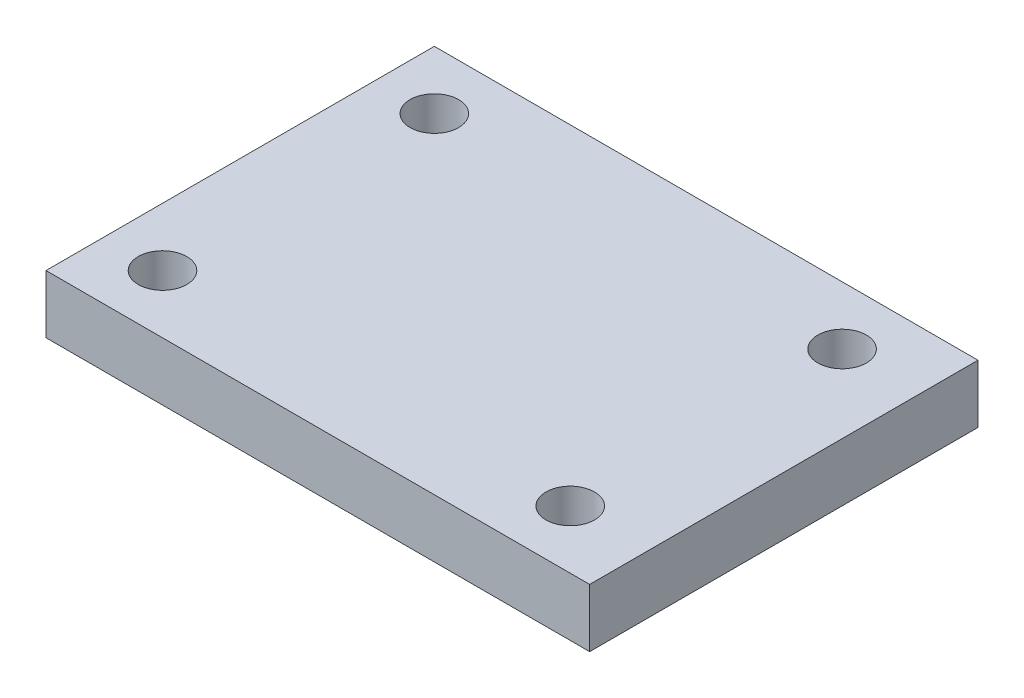
SolidWorks part; units mm, degrees
material "1060 Alloy"
ref_plane "Front Plane" through (0, 0, 0) normal (0, 0, 1) x (1, 0, 0)
ref_plane "Top Plane" through (0, 0, 0) normal (0, 1, 0) x (1, 0, 0)
ref_plane "Right Plane" through (0, 0, 0) normal (1, 0, 0) x (0, 0, -1)
sketch "Sketch1" plane through (0, 0, 0) normal (0, 1, 0) x (1, 0, 0)
  line L1 (-14, -10) -> (14, -10)
  line L2 (-14, -10) -> (-14, 10)
  line L3 (-14, 10) -> (14, 10)
  line L4 (14, -10) -> (14, 10)
  line L5 (-14, -10) -> (14, 10) construction
  line L6 (-14, 10) -> (14, -10) construction
  point P0 (0, 0)
  dimension "D1" = 20
  dimension "D2" = 28
extrude "Boss-Extrude1" add sketch "Sketch1" along normal blind 3
hole_wizard "M3 Tapped Hole1" positions "Sketch2" profile "Sketch3" tap size "M3" standard "DIN" end condition through all
sketch "Sketch2" plane through (0, 3, 0) normal (0, 1, 0) x (1, 0, 0)
  line L0 (-14, 10) -> (-14, -10) construction
  line L1 (14, 10) -> (-14, 10) construction
  point P0 (-11, 7)
  point P2 (10, 7)
  point P4 (10, -7)
  point P6 (-11, -7)
  dimension "D1" = 21
  dimension "D2" = 3
  dimension "D3" = 14
  dimension "D4" = 3
sketch "Sketch3" plane through (-11, 3, -7) normal (1, 0, 0) x (0, 0, 1)
  line L0 (0, 0) -> (0, 3)
  line L1 (0, 3) -> (1.25, 3)
  line L2 (1.25, 3) -> (1.25, 0)
  line L5 (1.25, 0) -> (0, 0)
  line L11 (0, -6.35) -> (0, 107.95) construction
  dimension "Thru Tap Drill Dia." = 2.5
  dimension "Thru Tap Drill Depth" = 3
cosmetic thread "Hole Thread1" parameters "D2"=3
cosmetic thread "Hole Thread2" parameters "D2"=3
cosmetic thread "Hole Thread3" parameters "D2"=3
cosmetic thread "Hole Thread4" parameters "D2"=3
